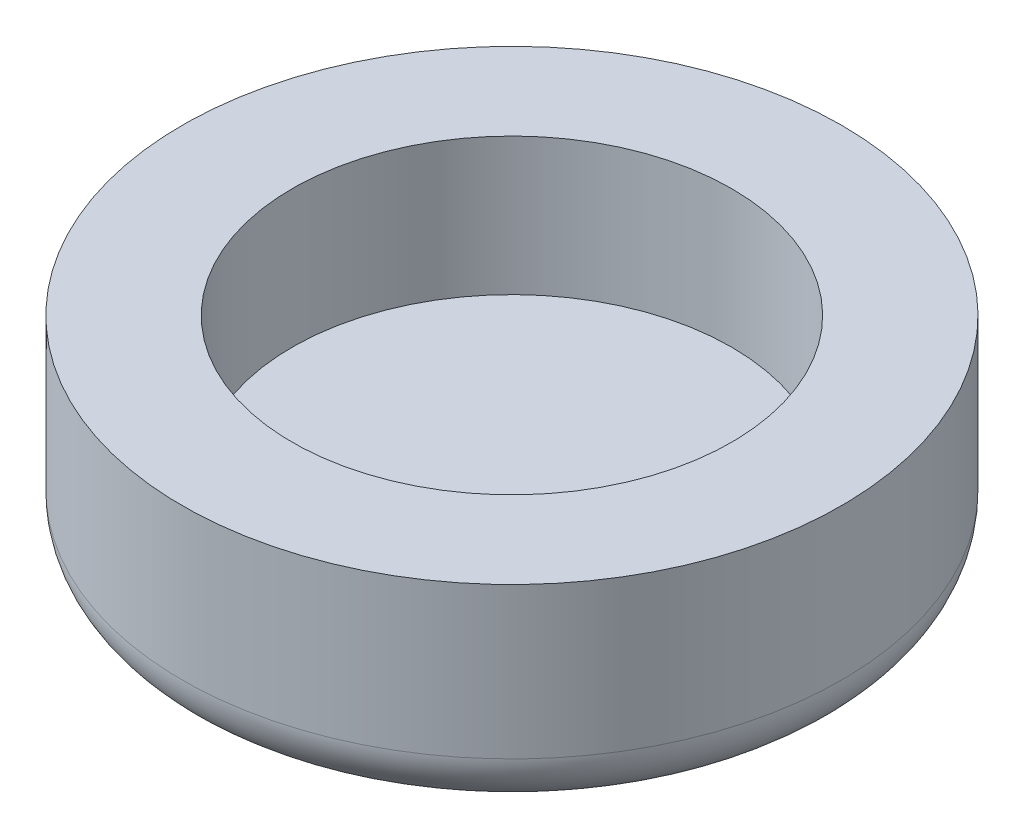
SolidWorks part; units mm, degrees
ref_plane "Front Plane" through (0, 0, 0) normal (0, 0, 1) x (1, 0, 0)
ref_plane "Top Plane" through (0, 0, 0) normal (0, 1, 0) x (1, 0, 0)
ref_plane "Right Plane" through (0, 0, 0) normal (1, 0, 0) x (0, 0, -1)
sketch "Sketch1" plane through (0, 0, 0) normal (0, 0, 1) x (1, 0, 0)
  line L0 (0, 0) -> (0, 2.7905) construction
  line L1 (0, 0) -> (2.4, 0)
  line L2 (2.4, 0) -> (2.4, 1.5)
  line L3 (2.4, 1.5) -> (1.6, 1.5)
  line L4 (1.6, 1.5) -> (1.6, 0.5)
  line L5 (1.6, 0.5) -> (0, 0.5)
  line L6 (0, 0.5) -> (0, 0)
  dimension "D1" = 0.5
  dimension "D2" = 1
  dimension "D3" = 1.6
  dimension "D4" = 0.8
revolve "Revolve1" add sketch "Sketch1" angle 360 about L0
fillet "Fillet1" radius 0.4 1 edges at (0, 0, -2.4)
